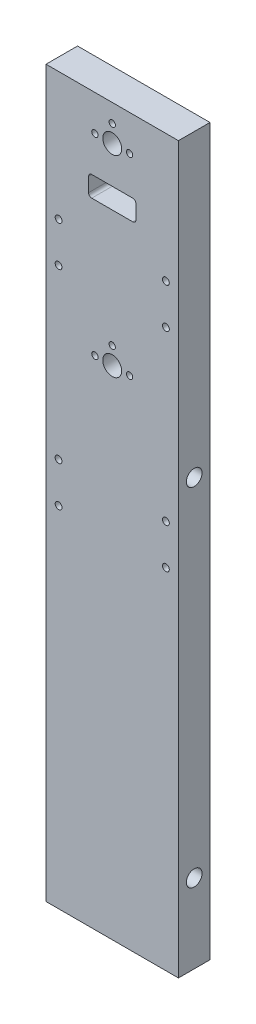
SolidWorks part; units mm, degrees
ref_plane "Front Plane" through (0, 0, 0) normal (0, 0, 1) x (1, 0, 0)
ref_plane "Top Plane" through (0, 0, 0) normal (0, 1, 0) x (1, 0, 0)
ref_plane "Right Plane" through (0, 0, 0) normal (1, 0, 0) x (0, 0, -1)
sketch "Sketch1" plane through (0, 0, 0) normal (0, 0, 1) x (1, 0, 0)
  line L0 (-18, -106) -> (18, -106) construction
  line L1 (42, 38.575) -> (42, -421.425)
  line L2 (-42, 38.575) -> (42, 38.575)
  line L3 (-42, 38.575) -> (-42, -421.425)
  line L6 (-18, 16) -> (18, 16) construction
  line L11 (-32.5, 38.575) -> (32.5, 38.575) construction
  line L14 (-42, -421.425) -> (42, -421.425)
  line L25 (-32.5, -371.425) -> (-32.5, 38.575) construction
  line L26 (-82.5, -421.425) -> (82.5, -421.425) construction
  line L27 (32.5, -371.425) -> (32.5, 38.575) construction
  line L28 (-32.5, -371.425) -> (32.5, -371.425) construction
  line L29 (82.5, -421.425) -> (82.5, 88.575) construction
  line L30 (-82.5, -421.425) -> (-82.5, 88.575) construction
  line L31 (-82.5, 88.575) -> (82.5, 88.575) construction
  circle A5 centre (0, -106) radius 6
  circle A6 centre (0, -106) radius 11 construction
  circle A7 centre (11, -106) radius 2
  circle A10 centre (0, -95) radius 2
  circle A12 centre (0, 16) radius 6
  circle A13 centre (11, 16) radius 2
  circle A14 centre (-11, -106) radius 2
  circle A15 centre (0, 27) radius 2
  circle A16 centre (-11, 16) radius 2
  circle A17 centre (0, 16) radius 11 construction
  dimension "D9" = 2
  dimension "D2" = 84
  dimension "D3" = 460
  dimension "D10" = 122
extrude "Boss-Extrude1" add sketch "Sketch1" along normal blind 20
sketch "Sketch2" plane through (0, 0, 0) normal (1, 0, 0) x (0, 0, -1)
  line L0 (-20, -371.425) -> (0, -371.425) construction
  line L2 (-20, -151.425) -> (0, -151.425) construction
  circle A0 centre (-10, -151.425) radius 5
  circle A1 centre (-10, -371.425) radius 5
extrude "Cut-Extrude1" cut sketch "Sketch2" against normal mid plane 100
sketch "Sketch3" plane through (0, 0, 0) normal (0, 0, 1) x (1, 0, 0)
  line L1 (-12.7, -67.117) -> (-41.656, -67.117)
  line L2 (41.656, -67.117) -> (12.7, -67.117)
  line L3 (-41.656, -22.9207) -> (-41.656, -67.117)
  line L4 (41.656, -22.9207) -> (41.656, -67.117)
  line L5 (12.7, -67.117) -> (12.7, -54.417)
  line L6 (34.036, -67.117) -> (34.036, -36.2127) construction
  line L7 (-12.7, -54.417) -> (-12.7, -67.117)
  line L8 (-34.036, -67.117) -> (-34.036, -36.2127) construction
  line L9 (39.497, -56.957) -> (28.575, -56.957) construction
  line L10 (30.734, -59.116) -> (37.338, -59.116)
  line L11 (37.338, -54.798) -> (30.734, -54.798)
  line L12 (-39.497, -31.557) -> (-28.575, -31.557) construction
  line L13 (30.734, -33.716) -> (37.338, -33.716)
  line L14 (-39.497, -56.957) -> (-28.575, -56.957) construction
  line L15 (39.497, -31.557) -> (28.575, -31.557) construction
  line L16 (37.338, -29.398) -> (30.734, -29.398)
  line L17 (-37.338, -29.398) -> (-30.734, -29.398)
  line L18 (-30.734, -33.716) -> (-37.338, -33.716)
  line L19 (-37.338, -54.798) -> (-30.734, -54.798)
  line L20 (-30.734, -59.116) -> (-37.338, -59.116)
  line L21 (30.988, -16.7615) -> (41.656, -22.9207)
  line L22 (30.988, -16.7615) -> (30.988, -11.999)
  line L23 (30.988, -11.999) -> (-30.988, -11.999)
  line L24 (-30.988, -11.999) -> (-30.988, -16.7615)
  line L25 (-30.988, -16.7615) -> (-41.656, -22.9207)
  line L26 (0, -11.999) -> (-19.4236, -11.999) construction
  line L27 (30.988, -16.7615) -> (-30.988, -16.7615) construction
  line L28 (0, 10) -> (-9.559, 10) construction
  arc A0 (37.338, -33.716) -> (37.338, -29.398) centre (37.338, -31.557) ccw
  arc A1 (30.734, -59.116) -> (30.734, -54.798) centre (30.734, -56.957) cw
  arc A2 (12.7, -54.417) -> (-12.7, -54.417) centre (0, -54.417) ccw
  arc A3 (37.338, -59.116) -> (37.338, -54.798) centre (37.338, -56.957) ccw
  arc A4 (-30.734, -33.716) -> (-30.734, -29.398) centre (-30.734, -31.557) ccw
  arc A5 (30.734, -33.716) -> (30.734, -29.398) centre (30.734, -31.557) cw
  arc A6 (-37.338, -59.116) -> (-37.338, -54.798) centre (-37.338, -56.957) cw
  arc A7 (-30.734, -59.116) -> (-30.734, -54.798) centre (-30.734, -56.957) ccw
  arc A8 (-37.338, -33.716) -> (-37.338, -29.398) centre (-37.338, -31.557) cw
  circle A9 centre (0, 16) radius 6 construction
  circle A12 centre (0, 16) radius 15 construction
  dimension "D1" = 68.072
  dimension "D2" = 83.312
  dimension "D3" = 12.7
sketch "Sketch4" plane through (0, 0, 0) normal (0, 0, 1) x (1, 0, 0)
  line L0 (0, -4.7625) -> (0, -30.7793) construction
  line L6 (34.036, -78.117) -> (34.036, -47.2127) construction
  line L8 (-34.036, -78.117) -> (-34.036, -47.2127) construction
  circle A2 centre (34.036, -42.557) radius 2.159
  circle A9 centre (34.036, -67.957) radius 2.159
  circle A10 centre (-34.036, -67.957) radius 2.159
  circle A11 centre (-34.036, -42.557) radius 2.159
  dimension "D1" = 68.072
extrude "Cut-Extrude2" cut sketch "Sketch4" along normal blind 20
sketch "Sketch5" plane through (0, 0, 0) normal (0, 0, 1) x (1, 0, 0)
  line L0 (15, -18.4995) -> (15, -9.4995)
  line L2 (-13, -20.4995) -> (13, -20.4995)
  line L4 (-15, -18.4995) -> (-15, -9.4995)
  line L5 (13, -7.4995) -> (-13, -7.4995)
  arc A0 (15, -9.4995) -> (13, -7.4995) centre (13, -9.4995) ccw
  arc A1 (-13, -7.4995) -> (-15, -9.4995) centre (-13, -9.4995) ccw
  arc A2 (-13, -20.4995) -> (-15, -18.4995) centre (-13, -18.4995) cw
  arc A3 (13, -20.4995) -> (15, -18.4995) centre (13, -18.4995) ccw
  dimension "D1" = 2
extrude "Cut-Extrude3" cut sketch "Sketch5" along normal blind 20
sketch "Sketch6" plane through (0, 0, 0) normal (0, 0, 1) x (1, 0, 0)
  line L6 (34.036, -210.118) -> (34.036, -179.2137) construction
  line L8 (-34.036, -210.118) -> (-34.036, -179.2137) construction
  line L28 (0, 10) -> (-9.559, 10) construction
  circle A2 centre (34.036, -174.558) radius 2.159
  circle A9 centre (-34.036, -174.558) radius 2.159
  circle A10 centre (-34.036, -199.958) radius 2.159
  circle A11 centre (34.036, -199.958) radius 2.159
  circle A12 centre (0, 16) radius 15 construction
extrude "Cut-Extrude4" cut sketch "Sketch6" along normal blind 20
